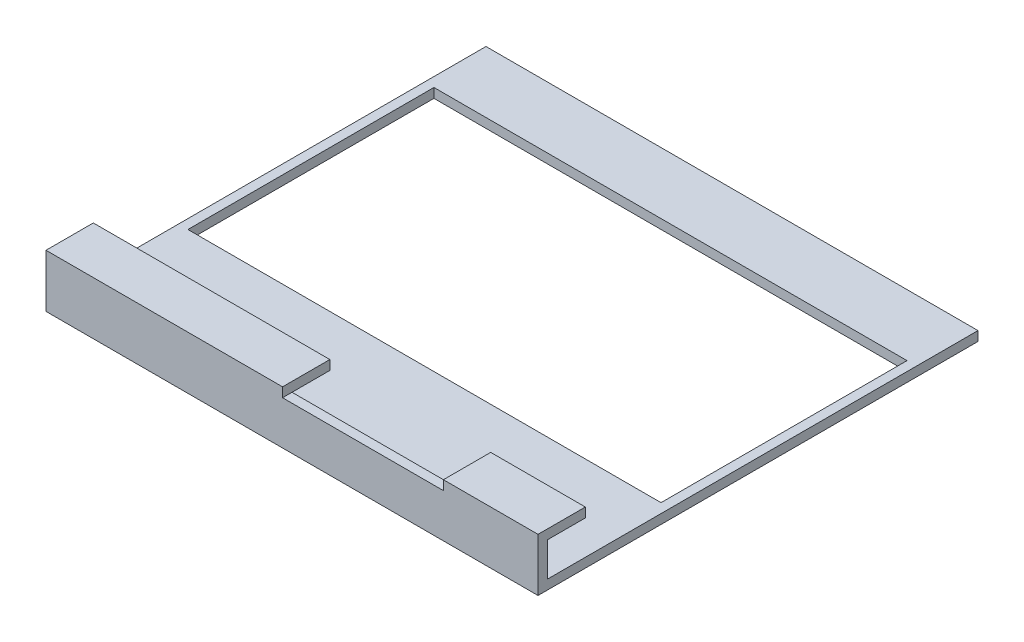
SolidWorks part; units mm, degrees
ref_plane "Front Plane" through (0, 0, 0) normal (0, 0, 1) x (1, 0, 0)
ref_plane "Top Plane" through (0, 0, 0) normal (0, 1, 0) x (1, 0, 0)
ref_plane "Right Plane" through (0, 0, 0) normal (1, 0, 0) x (0, 0, -1)
sketch "Sketch1" plane through (0, 0, 0) normal (1, 0, 0) x (0, 0, -1)
  line L1 (0, 0) -> (93, 0)
  line L2 (0, 0) -> (0, 11.2)
  line L3 (0, 11.2) -> (10, 11.2)
  line L4 (93, 0) -> (93, 2)
  line L7 (93, 2) -> (2, 2)
  line L8 (10, 11.2) -> (10, 9.2)
  line L11 (10, 9.2) -> (2, 9.2)
  line L12 (2, 2) -> (2, 9.2)
  point P1 (5.4706, 7.1471)
  dimension "D1" = 7.2
  dimension "D2" = 8
  dimension "D3" = 91
  dimension "D4" = 2
  dimension "D5" = 2
  dimension "D6" = 2
extrude "Boss-Extrude1" add sketch "Sketch1" along normal blind 104
sketch "Sketch2" plane through (0, 11.2, 0) normal (0, 1, 0) x (1, 0, 0)
  line L0 (104, 10) -> (0, 10) construction
  line L1 (50, 10) -> (84, 10)
  line L2 (50, 10) -> (50, 0)
  line L3 (50, 0) -> (84, 0)
  line L4 (84, 10) -> (84, 0)
  line L5 (0, 10) -> (0, 0) construction
  line L6 (104, 10) -> (104, 0) construction
  line L8 (104, 0) -> (0, 0) construction
  dimension "D1" = 50
  dimension "D2" = 20
extrude "Cut-Extrude1" cut sketch "Sketch2" against normal up to surface (2 mm away) up to face at (52, 9.2, -6)
sketch "Sketch3" plane through (0, 2, 0) normal (0, 1, 0) x (1, 0, 0)
  line L1 (2, 80) -> (102, 80)
  line L2 (2, 80) -> (2, 28)
  line L3 (2, 28) -> (102, 28)
  line L4 (102, 80) -> (102, 28)
  line L9 (104, 93) -> (0, 93) construction
  line L10 (104, 2) -> (0, 2) construction
  line L11 (104, 93) -> (104, 2) construction
  line L12 (0, 93) -> (0, 2) construction
  dimension "D1" = 13
  dimension "D2" = 26
  dimension "D3" = 2
  dimension "D4" = 2
extrude "Cut-Extrude2" cut sketch "Sketch3" against normal up to next
